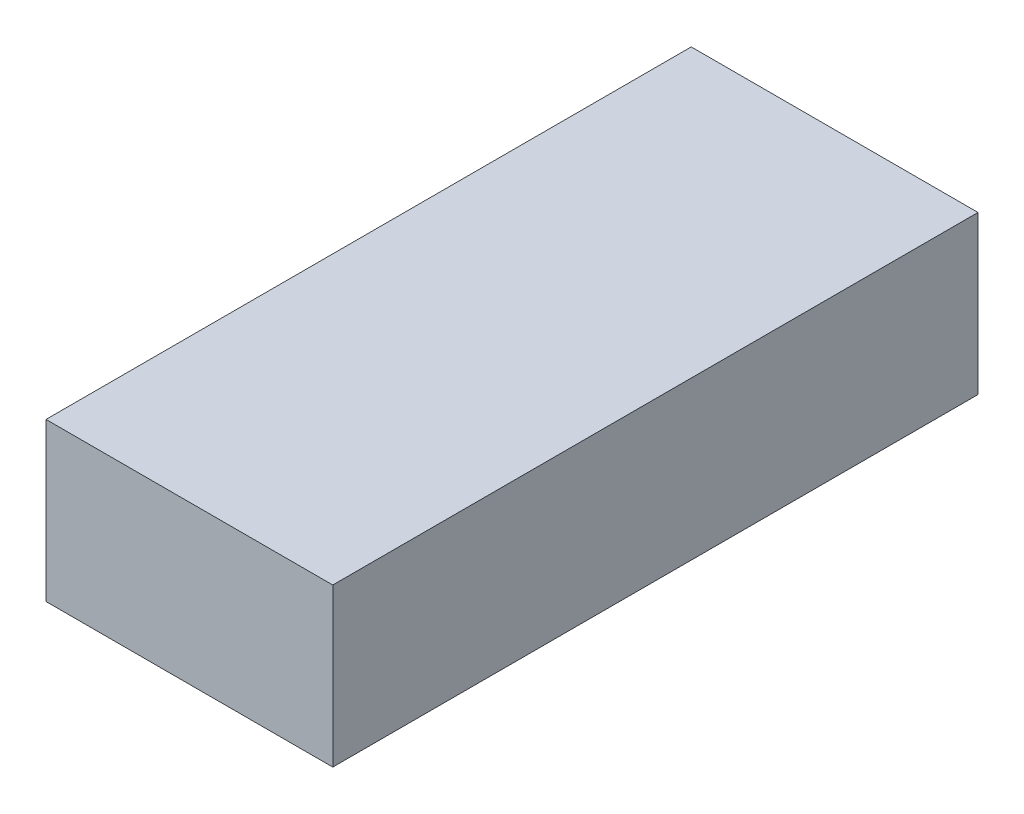
SolidWorks part; units mm, degrees
ref_plane "Front Plane" through (0, 0, 0) normal (0, 0, 1) x (1, 0, 0)
ref_plane "Top Plane" through (0, 0, 0) normal (0, 1, 0) x (1, 0, 0)
ref_plane "Right Plane" through (0, 0, 0) normal (1, 0, 0) x (0, 0, -1)
sketch "Sketch1" plane through (0, 0, 0) normal (0, 0, 1) x (1, 0, 0)
  line L1 (0, 0) -> (20, 0)
  line L2 (0, 0) -> (0, 11)
  line L3 (0, 11) -> (20, 11)
  line L4 (20, 0) -> (20, 11)
  dimension "D1" = 20
  dimension "D2" = 11
extrude "Boss-Extrude1" add sketch "Sketch1" along normal blind 45
